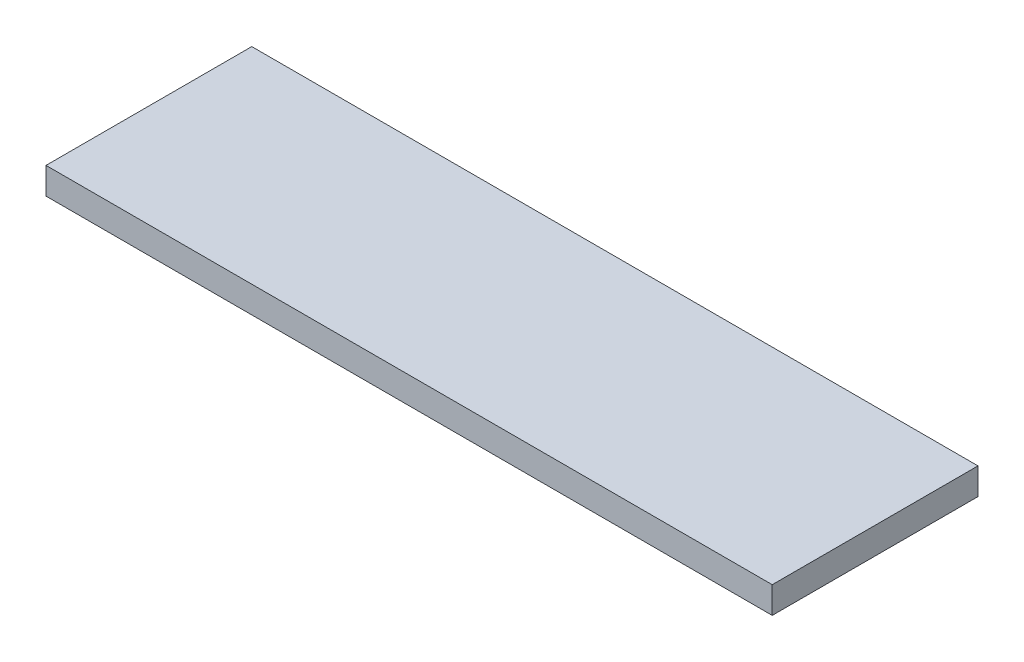
SolidWorks part; units mm, degrees
material "Pino"
ref_plane "Alzado" through (0, 0, 0) normal (0, 0, 1) x (1, 0, 0)
ref_plane "Planta" through (0, 0, 0) normal (0, 1, 0) x (1, 0, 0)
ref_plane "Vista lateral" through (0, 0, 0) normal (1, 0, 0) x (0, 0, -1)
sketch "Croquis1" plane through (0, 0, 0) normal (0, 1, 0) x (1, 0, 0)
  line L0 (-246.8983, -56.0456) -> (-246.8983, 113.9544)
  line L1 (-246.8983, 113.9544) -> (353.1017, 113.9544)
  line L2 (353.1017, 113.9544) -> (353.1017, -56.0456)
  line L3 (353.1017, -56.0456) -> (-246.8983, -56.0456)
  dimension "D1" = 170
  dimension "D2" = 600
extrude "Saliente-Extruir1" add sketch "Croquis1" along normal blind 22
